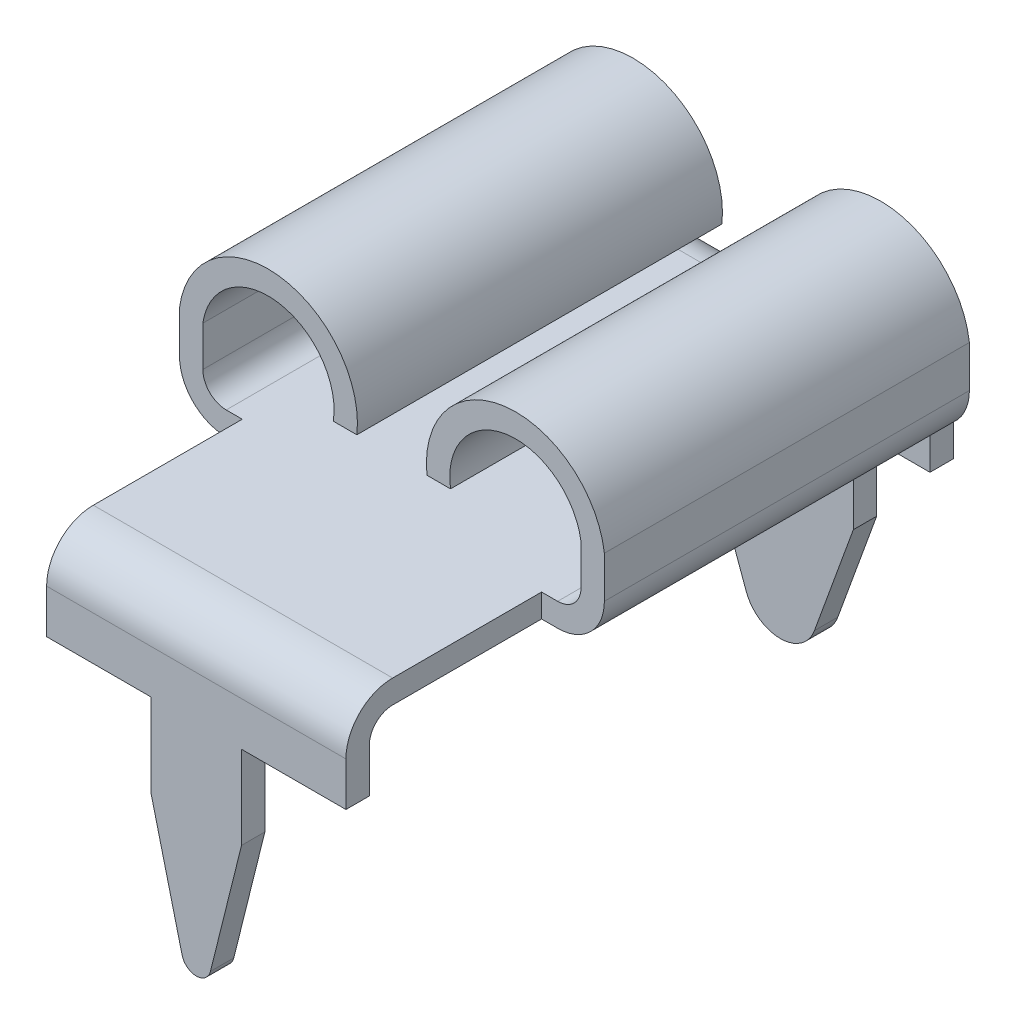
SolidWorks part; units mm, degrees
material "Brass"
ref_plane "Plane1" through (0, 0, 0) normal (0, 0, 1) x (1, 0, 0)
ref_plane "Plane2" through (0, 0, 0) normal (0, 1, 0) x (1, 0, 0)
ref_plane "Plane3" through (0, 0, 0) normal (1, 0, 0) x (0, 0, -1)
sketch "Sketch1" plane through (0, 0, 0) normal (1, 0, 0) x (0, 0, -1)
  line L1 (-0.2032, 0) -> (-0.2032, 5.3848)
  line L2 (-0.2032, 5.3848) -> (10.3632, 5.3848)
  line L4 (0.2032, 0) -> (0.2032, 4.9784)
  line L5 (0.2032, 4.9784) -> (9.9568, 4.9784)
  line L6 (9.9568, 4.9784) -> (9.9568, 0)
  line L9 (10.3632, 5.3848) -> (10.3632, 0)
  line L10 (50, 0) -> (-50, 0) construction
  line L11 (10.1528, -0.4735) -> (10.1528, 7.3039) construction
  line L12 (0, 50) -> (0, -50) construction
  line L13 (-0.2032, 0) -> (0.2032, 0)
  line L14 (10.3632, 0) -> (9.9568, 0)
  dimension "D1" = 0.4064
  dimension "D2" = 5.3848
  dimension "D4" = 10.1528
  dimension "D5" = 0.2104
  dimension "D3" = 0.2032
extrude "Boss-Extrude1" add sketch "Sketch1" along normal blind 5.207
sketch "Sketch2" plane through (0, 0, -10.3632) normal (0, 0, -1) x (-1, 0, 0)
  line L0 (-6.427, 3.81) -> (0.8085, 3.81) construction
  line L1 (-5.207, 5.3848) -> (0, 5.3848) construction
  line L2 (-2.6035, 0) -> (-2.6035, 6.9123) construction
  line L3 (-5.207, 0) -> (0, 0) construction
  line L4 (-1.3335, 2.2786) -> (-1.3335, 3.81)
  line L5 (-3.8735, 2.2786) -> (-3.8735, 3.81)
  line L6 (-1.3335, 3.81) -> (0, 3.81)
  line L7 (-3.8735, 3.81) -> (-5.207, 3.81)
  line L8 (-5.207, 0) -> (-5.207, 5.3848) construction
  line L9 (0, 0) -> (0, 5.3848) construction
  line L10 (-5.207, -0.2714) -> (-5.207, 3.81)
  line L11 (0, -0.2714) -> (0, 3.81)
  line L13 (-5.207, -0.2714) -> (0, -0.2714)
  line L14 (-2.0103, 0.4191) -> (-1.3335, 2.2786)
  line L15 (-3.1967, 0.4191) -> (-3.8735, 2.2786)
  line L18 (-1.3335, 0) -> (-1.3335, 6.9123) construction
  line L19 (-3.8735, 0) -> (-3.8735, 6.9123) construction
  arc A0 (-3.1967, 0.4191) -> (-2.0103, 0.4191) centre (-2.6035, 0.635) ccw
  dimension "D6" = 0.635
  dimension "D5" = 0.6313
  dimension "D1" = 1.5748
  dimension "D7" = 20
  dimension "D8" = 40
  dimension "D2" = 1.27
  dimension "D3" = 1.27
extrude "Cut-Extrude1" cut sketch "Sketch2" against normal blind 5.207
sketch "Sketch4" plane through (0, 0, 0.2032) normal (0, 0, 1) x (1, 0, 0)
  line L0 (3.8735, 3.81) -> (5.207, 3.81) construction
  line L4 (0, 5.3848) -> (0, 0)
  line L5 (0, 0) -> (5.207, 0)
  line L6 (5.207, 0) -> (5.207, 5.3848)
  line L7 (5.207, 5.3848) -> (0, 5.3848)
  line L8 (0, 3.81) -> (0, -0.2936)
  line L9 (0, -0.2936) -> (5.207, -0.2936)
  line L10 (5.207, -0.2936) -> (5.207, 3.81)
  line L11 (5.207, 0) -> (0, 0) construction
  line L13 (0, 3.81) -> (1.3335, 3.81) construction
  line L14 (3.3909, 3.81) -> (5.207, 3.81)
  line L15 (2.85, 0.1926) -> (3.3909, 2.3622)
  line L16 (2.357, 0.1926) -> (1.8161, 2.3622)
  line L17 (2.6035, 5.3848) -> (2.6035, -0.6944) construction
  line L19 (0, 3.81) -> (1.8161, 3.81)
  line L20 (5.207, 5.3848) -> (0, 5.3848) construction
  line L21 (3.3909, 2.3622) -> (3.3909, 3.81)
  line L22 (1.8161, 3.81) -> (1.8161, 2.3622)
  line L24 (0, 5.3848) -> (0, 0) construction
  arc A2 (2.357, 0.1926) -> (2.85, 0.1926) centre (2.6035, 0.254) ccw
  dimension "D2" = 0.254
  dimension "D3" = 0.254
  dimension "D4" = 2.6035
  dimension "D5" = 1.5748
  dimension "D6" = 0.7874
  dimension "D7" = 14
  dimension "D8" = 14
  dimension "D1" = 0
extrude "Cut-Extrude2" cut sketch "Sketch4" against normal blind 5.207
fillet "Fillet1" radius 0.4064 2 edges at (2.6035, 4.9784, -0.2032) (2.6035, 4.9784, -9.9568)
fillet "Fillet2" radius 0.8128 2 edges at (2.6035, 5.3848, -10.3632) (2.6035, 5.3848, 0.2032)
ref_plane "Plane4" through (0, 0, -9.5504) normal (0, 0, -1) x (-1, 0, 0)
sketch "Sketch5" plane through (0, 0, -9.5504) normal (0, 0, -1) x (-1, 0, 0)
  line L0 (-2.6035, 0.635) -> (-2.6035, 7.0398) construction
  line L1 (1.0922, 5.7912) -> (1.0922, 6.5159)
  line L2 (-5.207, 5.3848) -> (0, 5.3848) construction
  line L3 (-1.9939, 5.979) -> (-1.9939, 8.6885) construction
  line L4 (-1.5875, 5.979) -> (-1.5875, 8.6885) construction
  line L5 (-5.207, 7.874) -> (0, 7.874)
  line L6 (-5.207, 7.874) -> (0, 7.874) construction
  line L7 (-5.207, 6.1468) -> (0, 6.1468)
  line L8 (-5.207, 6.1468) -> (0, 6.1468) construction
  line L9 (-3.6195, 5.979) -> (-3.6195, 8.6885) construction
  line L10 (1.0922, 0.635) -> (1.0922, 7.0398) construction
  line L11 (0.6858, 5.7912) -> (0.6858, 6.4882)
  line L12 (-3.2131, 5.979) -> (-3.2131, 8.6885) construction
  line L13 (0, 4.9784) -> (0.2794, 4.9784)
  line L14 (0, 5.3848) -> (0.2794, 5.3848)
  line L15 (-1.9939, 6.1468) -> (-1.584, 6.1468)
  line L16 (0, 4.572) -> (0, 5.3848) construction
  line L17 (0, 4.9784) -> (0, 5.3848)
  line L18 (-5.207, 5.3848) -> (0.2794, 5.3848) construction
  line L19 (-5.207, 4.9784) -> (0.2794, 4.9784) construction
  line L20 (-5.207, 4.9784) -> (-5.207, 5.3848)
  line L21 (-3.2131, 6.1468) -> (-3.623, 6.1468)
  line L22 (-5.207, 5.3848) -> (-5.4864, 5.3848)
  line L23 (-5.207, 4.9784) -> (-5.4864, 4.9784)
  line L24 (-5.8928, 5.7912) -> (-5.8928, 6.4882)
  line L25 (-6.2992, 5.7912) -> (-6.2992, 6.5159)
  arc A0 (-1.9939, 6.1468) -> (1.0922, 6.5159) centre (-0.4495, 6.3199) cw
  arc A1 (1.0922, 5.7912) -> (0.2794, 4.9784) centre (0.2794, 5.7912) cw
  arc A2 (-1.584, 6.1468) -> (0.6858, 6.4882) centre (-0.4495, 6.3199) cw
  arc A3 (0.6858, 5.7912) -> (0.2794, 5.3848) centre (0.2794, 5.7912) cw
  arc A4 (-1.59, 6.1921) -> (0.6858, 6.4882) centre (-0.4495, 6.3199) cw construction
  arc A5 (-5.8928, 5.7912) -> (-5.4864, 5.3848) centre (-5.4864, 5.7912) ccw
  arc A6 (-3.623, 6.1468) -> (-5.8928, 6.4882) centre (-4.7575, 6.3199) ccw
  arc A7 (-6.2992, 5.7912) -> (-5.4864, 4.9784) centre (-5.4864, 5.7912) ccw
  arc A8 (-3.2131, 6.1468) -> (-6.2992, 6.5159) centre (-4.7575, 6.3199) ccw
  dimension "D10" = 1.5541
  dimension "D11" = 1.1477
  dimension "D6" = 0.8128
  dimension "D5" = 0.6096
  dimension "D2" = 3.6957
  dimension "D3" = 2.4892
  dimension "D4" = 0.762
  dimension "D8" = 0.4064
extrude "Boss-Extrude2" add sketch "Sketch5" against normal blind 6.35
